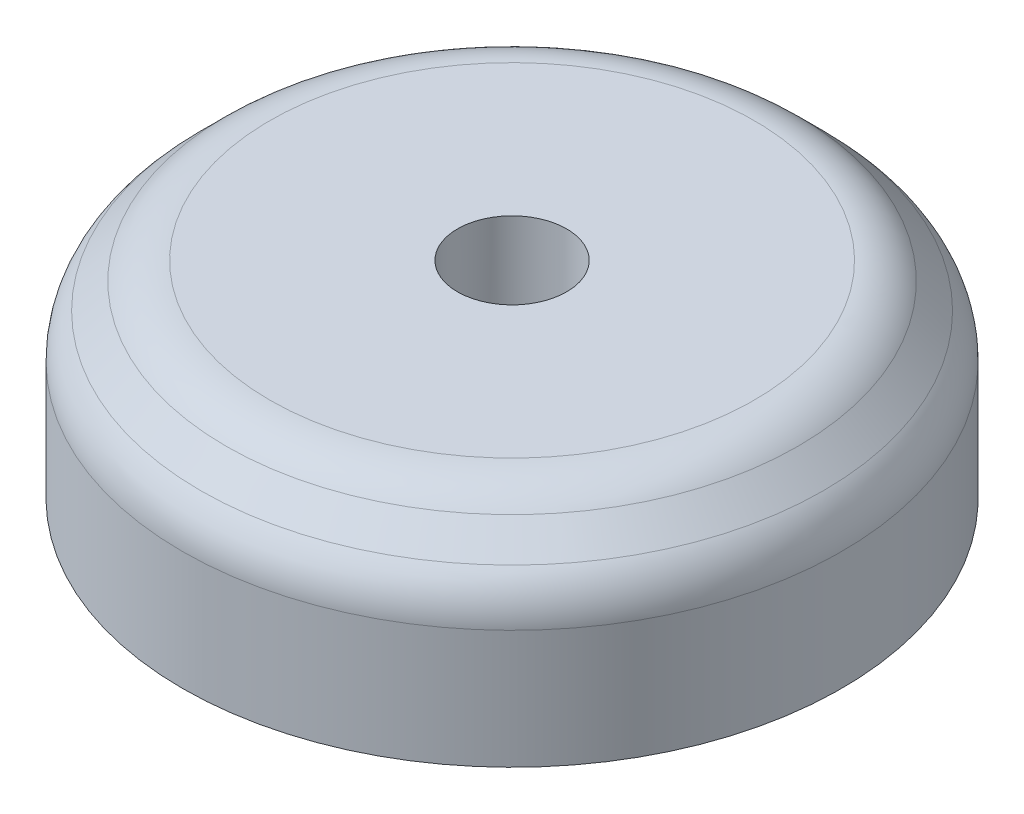
SolidWorks part; units mm, degrees
ref_plane "Front Plane" through (0, 0, 0) normal (0, 0, 1) x (1, 0, 0)
ref_plane "Top Plane" through (0, 0, 0) normal (0, 1, 0) x (1, 0, 0)
ref_plane "Right Plane" through (0, 0, 0) normal (1, 0, 0) x (0, 0, -1)
sketch "Sketch1" plane through (0, 0, 0) normal (0, 1, 0) x (1, 0, 0)
  circle A0 centre (0, 0) radius 16
  dimension "D1" = 32
extrude "Boss-Extrude1" add sketch "Sketch1" along normal blind 10
chamfer "Chamfer1" distance 3 angle 45 1 edges at (0, 10, 16)
fillet "Fillet1" radius 3 2 edges at (0, 7, 16) (0, 10, 13)
sketch "Sketch2" plane through (0, 10, 0) normal (0, 1, 0) x (1, 0, 0)
  circle A0 centre (0, 0) radius 2.65
  dimension "D1" = 5.3
extrude "Cut-Extrude1" cut sketch "Sketch2" against normal blind 10
sketch "Sketch3" plane through (0, 0, 0) normal (0, -1, 0) x (1, 0, 0)
  circle A0 centre (0, 0) radius 15
  dimension "D1" = 30
extrude "Cut-Extrude2" cut sketch "Sketch3" against normal blind 5
